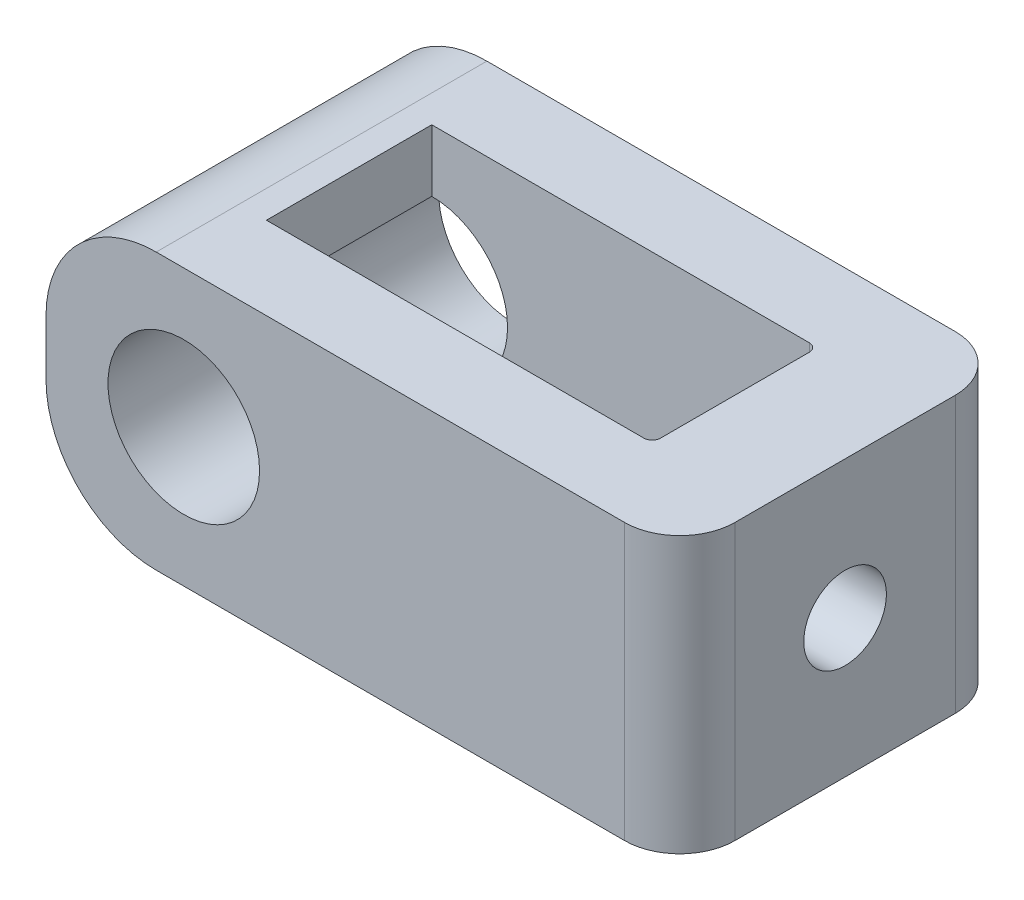
SolidWorks part; units mm, degrees
ref_plane "前视基准面" through (0, 0, 0) normal (0, 0, 1) x (1, 0, 0)
ref_plane "上视基准面" through (0, 0, 0) normal (0, 1, 0) x (1, 0, 0)
ref_plane "右视基准面" through (0, 0, 0) normal (1, 0, 0) x (0, 0, -1)
other "Configuration Table"
sketch "草图1" plane through (0, 0, 0) normal (0, 1, 0) x (1, 0, 0)
  line L0 (0, 0) -> (0, 11.3286) construction
  line L1 (0, 0) -> (15.6857, 0) construction
  line L2 (0, 3) -> (-19, 3)
  line L3 (-19, 3) -> (-19, 6)
  line L4 (-19, 6) -> (0, 6)
  line L5 (0, 6) -> (4, 6)
  line L6 (4, 6) -> (4, -6)
  line L7 (0, 3) -> (0, -3)
  line L8 (0, -6) -> (4, -6)
  line L9 (-19, -6) -> (0, -6)
  line L10 (-19, -3) -> (-19, -6)
  line L11 (0, -3) -> (-19, -3)
  point P12 (4, 0)
  dimension "D1" = 3
  dimension "D2" = 19
  dimension "D3" = 4
  dimension "D4" = 6
extrude "凸台-拉伸1" add sketch "草图1" along normal blind 10
sketch "草图2" plane through (0, 0, 6) normal (0, 0, 1) x (1, 0, 0)
  line L0 (-19, 10) -> (-19, 0) construction
  line L1 (-19, 10) -> (4, 10) construction
  circle A0 centre (-14, 5) radius 2.75
  dimension "D1" = 5.5
  dimension "D2" = 5
  dimension "D3" = 5
extrude "切除-拉伸1" cut sketch "草图2" against normal blind 16
fillet "圆角1" radius 4 4 edges at (-19, 0, -4.5) (-19, 10, -4.5) (-19, 0, 4.5) (-19, 10, 4.5)
sketch "草图3" plane through (4, 0, 0) normal (1, 0, 0) x (0, 0, -1)
  line L0 (-6, 10) -> (6, 10) construction
  line L1 (-6, 10) -> (-6, 0) construction
  circle A0 centre (0, 5) radius 1.5
  dimension "D1" = 3
  dimension "D2" = 5
  dimension "D3" = 6
extrude "切除-拉伸2" cut sketch "草图3" against normal blind 10
fillet "圆角2" radius 2 2 edges at (4, 5, -6) (4, 5, 6)
fillet "圆角3" radius 0.3 2 edges at (0, 5, 3) (0, 5, -3)
sketch "草图9" plane through (0, 0, -3) normal (0, 0, 1) x (1, 0, 0)
  line L0 (-19, 6) -> (-19, 4) construction
  line L1 (-19, 6) -> (-19, 4)
  line L2 (-15, 10) -> (-14, 10)
  line L3 (-15, 10) -> (2, 10) construction
  line L4 (-14, 10) -> (-14, 7.75)
  line L5 (-14, 2.25) -> (-14, 0)
  line L6 (-15, 0) -> (2, 0) construction
  line L7 (-14, 0) -> (-15, 0)
  arc A0 (-19, 4) -> (-15, 0) centre (-15, 4) ccw construction
  arc A1 (-15, 10) -> (-19, 6) centre (-15, 6) ccw construction
  arc A2 (-19, 4) -> (-15, 0) centre (-15, 4) ccw
  arc A3 (-15, 10) -> (-19, 6) centre (-15, 6) ccw
  circle A4 centre (-14, 5) radius 2.75 construction
  circle A5 centre (-14, 5) radius 2.75
  circle M2 centre (-14, 5) radius 2.75
  line M3 (-15, 0) -> (-0.3, 0)
  line M5 (-0.3, 10) -> (-15, 10)
  arc M6 (-15, 10) -> (-19, 6) centre (-15, 6) ccw
  line M7 (-19, 6) -> (-19, 4)
  arc M8 (-19, 4) -> (-15, 0) centre (-15, 4) ccw
extrude "凸台-拉伸4" add sketch "草图9" along normal blind 6 contours L5 L4 M2 M5 M6 M7 M8 M3
